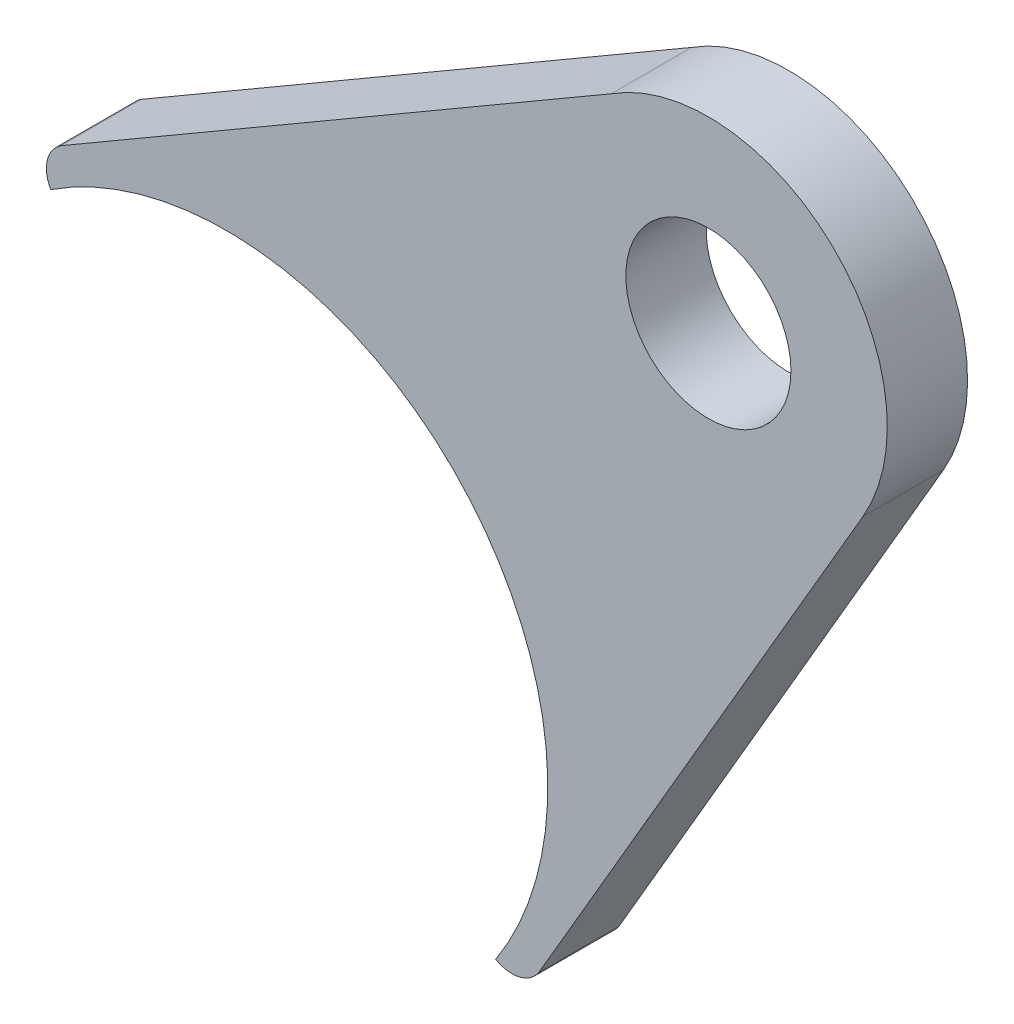
SolidWorks part; units mm, degrees
material "AISI 4340 Steel, annealed"
ref_plane "Front Plane" through (0, 0, 0) normal (0, 0, 1) x (1, 0, 0)
ref_plane "Top Plane" through (0, 0, 0) normal (0, 1, 0) x (1, 0, 0)
ref_plane "Right Plane" through (0, 0, 0) normal (1, 0, 0) x (0, 0, -1)
sketch "Sketch1" plane through (0, 0, 0) normal (0, 0, 1) x (1, 0, 0)
  line L4 (-6.5491, 12.3333) -> (15.2029, 24.9863)
  line L5 (12.3489, -6.5253) -> (25.1637, 15.4915)
  arc A0 (10.6407, -6.9329) -> (-6.9547, 10.6265) centre (0, 0) ccw
  circle A1 centre (19.05, 19.05) radius 3.2639
  arc A3 (10.6407, -6.9329) -> (12.3489, -6.5253) centre (11.2818, -5.8366) ccw
  arc A4 (25.1637, 15.4915) -> (15.2029, 24.9863) centre (19.05, 19.05) ccw
  arc A5 (-6.9547, 10.6265) -> (-6.5491, 12.3333) centre (-5.8584, 11.2675) cw
  dimension "D1" = 25.4
  dimension "D2" = 6.5278
  dimension "D5" = 14.1478
  dimension "D6" = 1.27
  dimension "D7" = 1.27
  dimension "D3" = 19.05
  dimension "D4" = 19.05
extrude "Boss-Extrude1" add sketch "Sketch1" along normal blind 3.175
ref_point "Point1"
